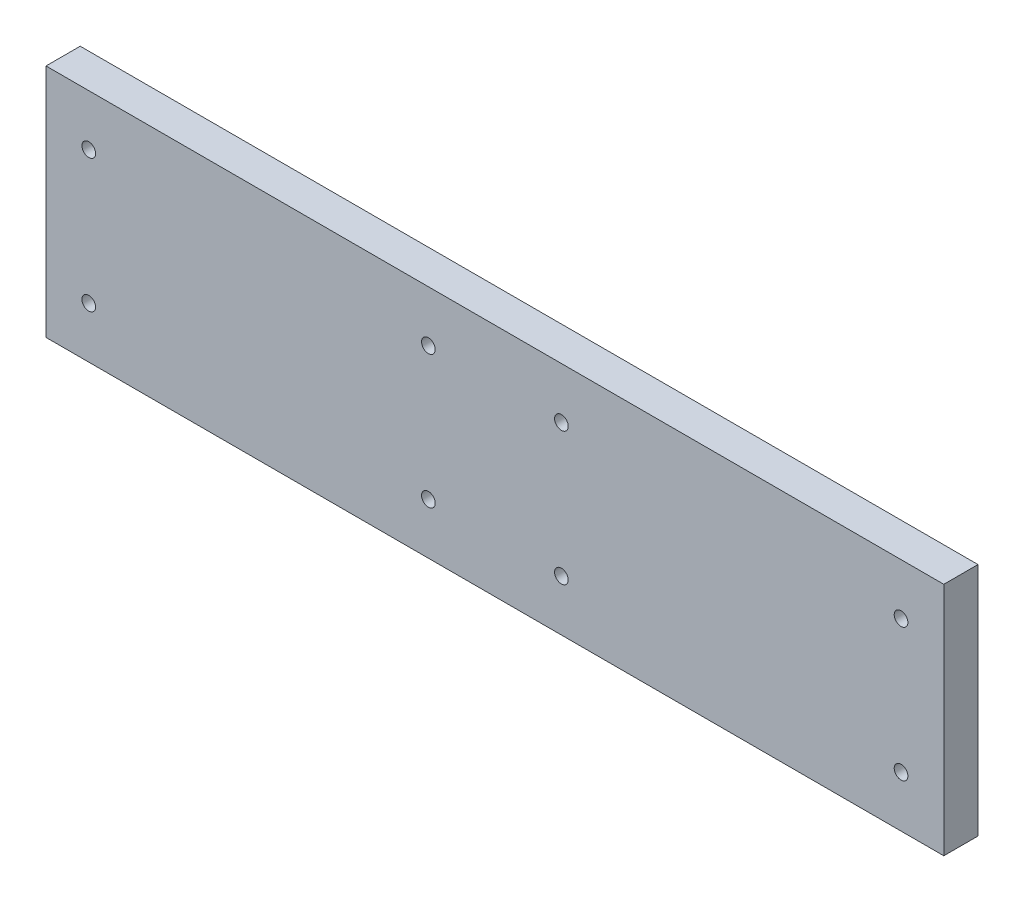
SolidWorks part; units mm, degrees
ref_plane "Front Plane" through (0, 0, 0) normal (0, 0, 1) x (1, 0, 0)
ref_plane "Top Plane" through (0, 0, 0) normal (0, 1, 0) x (1, 0, 0)
ref_plane "Right Plane" through (0, 0, 0) normal (1, 0, 0) x (0, 0, -1)
sketch "Sketch1" plane through (0, 0, 0) normal (0, 0, 1) x (1, 0, 0)
  line L1 (-105, -27.5) -> (105, -27.5)
  line L2 (-105, -27.5) -> (-105, 27.5)
  line L3 (-105, 27.5) -> (105, 27.5)
  line L4 (105, -27.5) -> (105, 27.5)
extrude "Boss-Extrude1" add sketch "Sketch1" along normal blind 8
sketch "Sketch2" plane through (0, 0, 0) normal (0, 0, 1) x (1, 0, 0)
  circle A0 centre (15.5563, 15.5563) radius 1.6
  circle A1 centre (-15.5563, 15.5563) radius 1.6
  circle A2 centre (-15.5563, -15.5563) radius 1.6
  circle A3 centre (15.5563, -15.5563) radius 1.6
  circle A4 centre (-95, 15.5563) radius 1.6
  circle A5 centre (-95, -15.5563) radius 1.6
  circle A6 centre (95, 15.5563) radius 1.6
  circle A7 centre (95, -15.5563) radius 1.6
extrude "Cut-Extrude2" cut sketch "Sketch2" along normal blind 9
